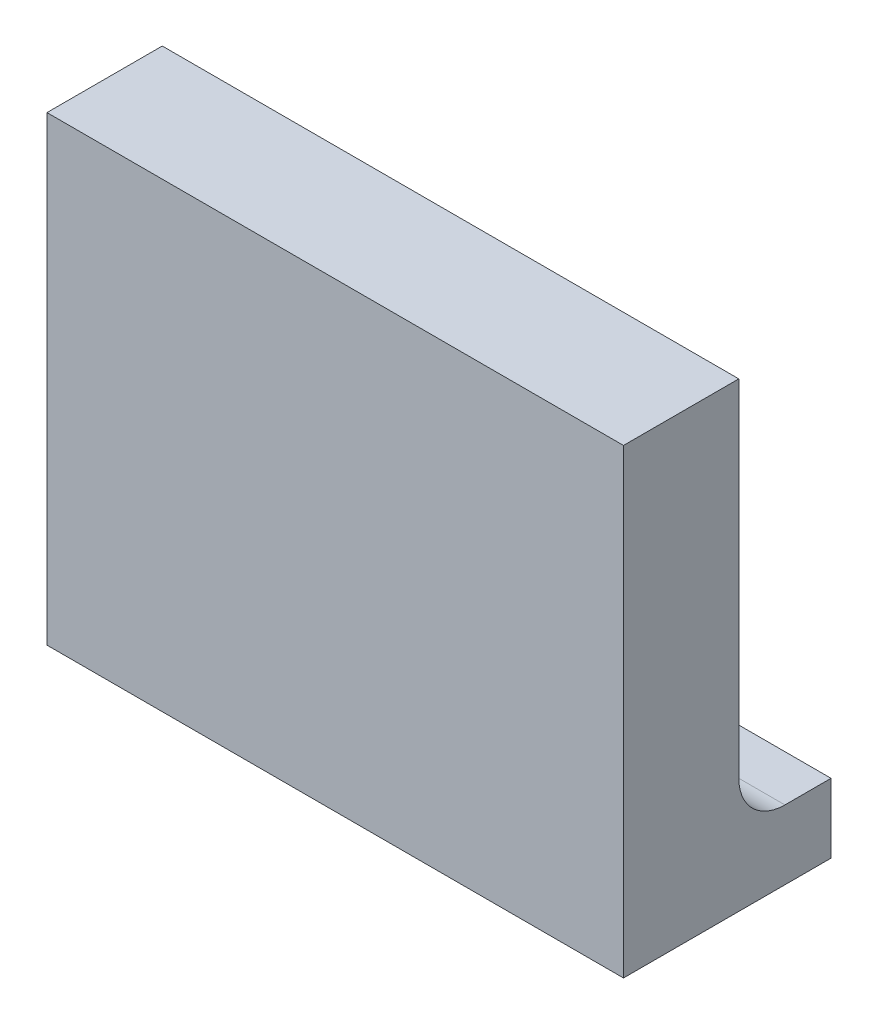
SolidWorks part; units mm, degrees
ref_plane "Front Plane" through (0, 0, 0) normal (0, 0, 1) x (1, 0, 0)
ref_plane "Top Plane" through (0, 0, 0) normal (0, 1, 0) x (1, 0, 0)
ref_plane "Right Plane" through (0, 0, 0) normal (1, 0, 0) x (0, 0, -1)
sketch "Sketch2" plane through (0, 0, 0) normal (1, 0, 0) x (0, 0, -1)
  line L0 (0, 0) -> (-9, 0)
  line L1 (-9, 0) -> (-9, 20)
  line L2 (-9, 20) -> (-4, 20)
  line L3 (-4, 20) -> (-4, 3)
  line L4 (-4, 3) -> (0, 3)
  line L5 (0, 3) -> (0, 0)
extrude "Boss-Extrude1" add sketch "Sketch2" along normal blind 25
fillet "Fillet1" radius 2 1 edges at (12.5, 3, 4)
